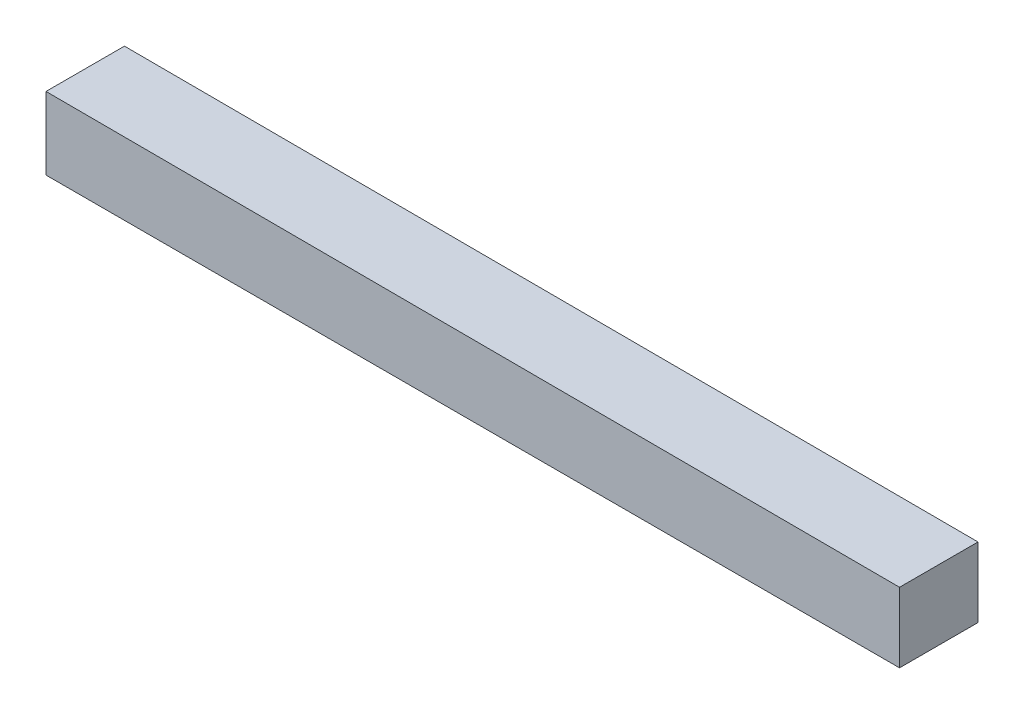
SolidWorks part; units mm, degrees
ref_plane "Front Plane" through (0, 0, 0) normal (0, 0, 1) x (1, 0, 0)
ref_plane "Top Plane" through (0, 0, 0) normal (0, 1, 0) x (1, 0, 0)
ref_plane "Right Plane" through (0, 0, 0) normal (1, 0, 0) x (0, 0, -1)
sketch "Sketch1" plane through (0, 0, 0) normal (0, 0, 1) x (1, 0, 0)
  line L0 (-28.8662, -4.6404) -> (25.5236, -4.6404)
  line L1 (25.5236, -4.6404) -> (25.5236, -0.1913)
  line L2 (25.5236, -0.1913) -> (-28.8662, -0.0235)
  line L3 (-28.8662, -0.0235) -> (-28.8662, -4.6404)
extrude "Boss-Extrude1" add sketch "Sketch1" along normal blind 5
